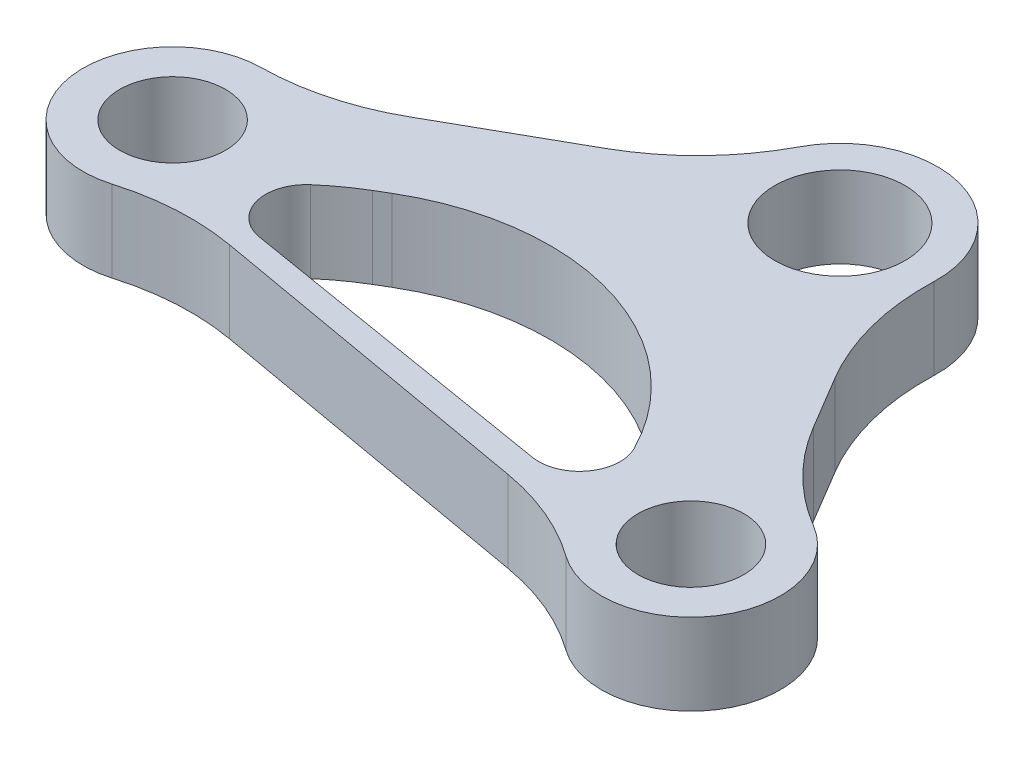
SolidWorks part; units mm, degrees
ref_plane "Front Plane" through (0, 0, 0) normal (0, 0, 1) x (1, 0, 0)
ref_plane "Top Plane" through (0, 0, 0) normal (0, 1, 0) x (1, 0, 0)
ref_plane "Right Plane" through (0, 0, 0) normal (1, 0, 0) x (0, 0, -1)
sketch "Sketch1" plane through (0, 0, 0) normal (0, 1, 0) x (1, 0, 0)
  line L0 (20.3127, -21.9922) -> (-19.8914, -15.3277)
  line L1 (34.3609, -1.5619) -> (30.4555, 4.9917)
  line L2 (-8.1351, 15.3299) -> (-23.4897, 6.6746)
  line L3 (-20.937, -17.9797) -> (20.6324, -25.3095)
  line L4 (-16.4342, -2.5402) -> (-17.9104, -3.4129)
  arc A0 (25.5899, -14.7984) -> (-16.4342, -2.5402) centre (-1.1673, -28.365) ccw
  circle A1 centre (-37.7094, -8.1882) radius 6.5
  arc A2 (32.8589, -30.4409) -> (20.6324, -25.3095) centre (15.423, -54.8537) ccw
  arc A3 (32.8589, -30.4409) -> (44.854, -12.0228) centre (39.2521, -21.4895) ccw
  arc A4 (34.3609, -1.5619) -> (44.854, -12.0228) centre (60.132, 13.7955) ccw
  arc A5 (26.2448, 21.3939) -> (30.4555, 4.9917) centre (56.2266, 20.3491) ccw
  arc A6 (26.2448, 21.3939) -> (3.6468, 27.4266) centre (14.2521, 21.8118) ccw
  arc A7 (-8.1351, 15.3299) -> (3.6468, 27.4266) centre (-22.8666, 41.4638) ccw
  arc A8 (-37.8467, 2.8109) -> (-23.4897, 6.6746) centre (-38.2212, 32.8086) ccw
  arc A9 (-37.8467, 2.8109) -> (-34.6072, -18.7417) centre (-37.7094, -8.1882) ccw
  arc A10 (-20.937, -17.9797) -> (-34.6072, -18.7417) centre (-26.1465, -47.5239) ccw
  circle A11 centre (14.2521, 21.8118) radius 8
  circle A12 centre (39.2521, -21.4895) radius 6.5
  arc A13 (20.3127, -21.9922) -> (25.5899, -14.7984) centre (21.1304, -17.0595) ccw
  arc A14 (-22.3598, -6.6265) -> (-19.8914, -15.3277) centre (-19.0737, -10.395) ccw
  arc A15 (-17.9104, -3.4129) -> (-22.3598, -6.6265) centre (-2.6434, -29.2377) ccw
  point P39 (0, 0)
  dimension "D1" = 16
  dimension "D2" = 13
  dimension "D3" = 30
  dimension "D4" = 11
  dimension "D5" = 12
  dimension "D6" = 5
  dimension "D7" = 3.6468
  dimension "D8" = 14.2521
  dimension "D9" = 15.423
  dimension "D10" = 20.3127
  dimension "D11" = 20.6324
  dimension "D12" = 21.1304
  dimension "D13" = 25.5899
  dimension "D14" = 26.2448
  dimension "D15" = 30.4555
  dimension "D16" = 32.8589
  dimension "D17" = 34.3609
  dimension "D18" = 2.6434
  dimension "D19" = 8.1351
  dimension "D20" = 16.4342
  dimension "D21" = 20.937
  dimension "D22" = 23.4897
  dimension "D23" = 2.8109
  dimension "D24" = 2.5402
extrude "Boss-Extrude1" add sketch "Sketch1" along normal blind 10
